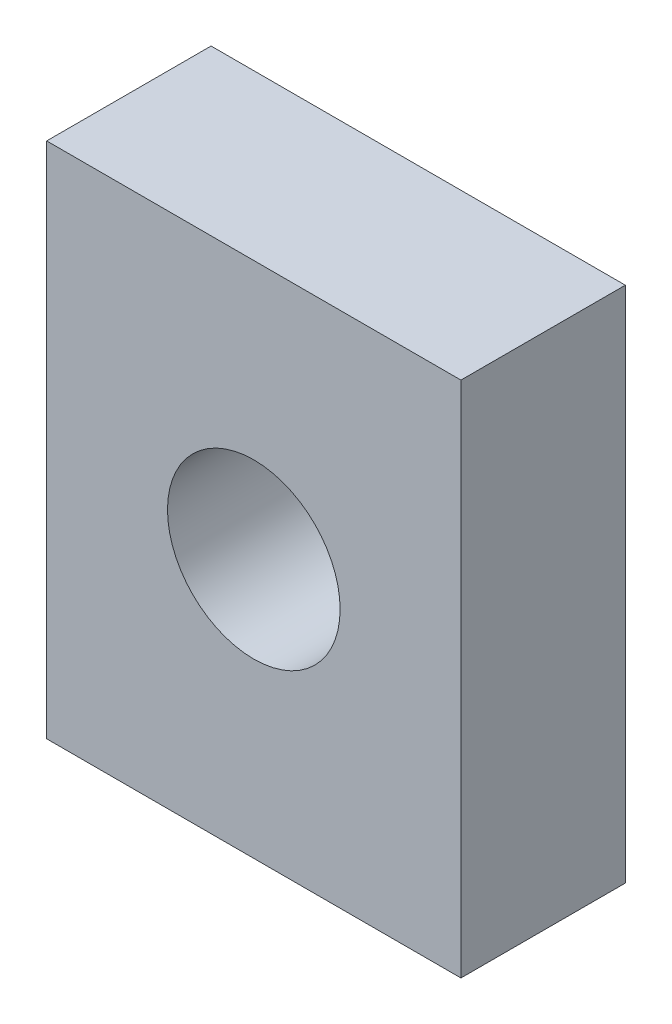
SolidWorks part; units mm, degrees
material "1023 碳钢板 (SS)"
ref_plane "前视基准面" through (0, 0, 0) normal (0, 0, 1) x (1, 0, 0)
ref_plane "上视基准面" through (0, 0, 0) normal (0, 1, 0) x (1, 0, 0)
ref_plane "右视基准面" through (0, 0, 0) normal (1, 0, 0) x (0, 0, -1)
sketch "草图1" plane through (0, 0, 0) normal (0, 0, 1) x (1, 0, 0)
  line L1 (-60, 75) -> (60, 75)
  line L2 (-60, 75) -> (-60, -75)
  line L3 (-60, -75) -> (60, -75)
  line L4 (60, 75) -> (60, -75)
  line L5 (-60, 75) -> (60, -75) construction
  line L6 (-60, -75) -> (60, 75) construction
  circle A0 centre (0, 0) radius 25
  point P0 (0, 0)
  dimension "D3" = 50
  dimension "D1" = 120
  dimension "D2" = 150
extrude "拉伸1" add sketch "草图1" along normal blind 47.619
